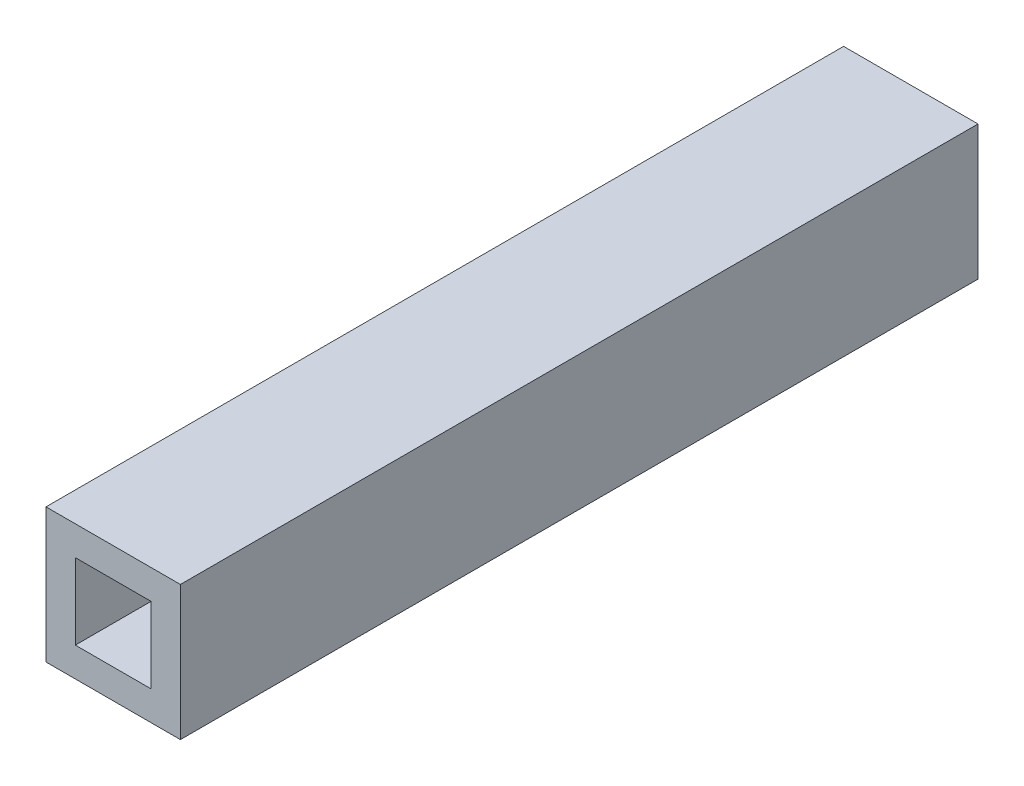
SolidWorks part; units mm, degrees
ref_plane "Front Plane" through (0, 0, 0) normal (0, 0, 1) x (1, 0, 0)
ref_plane "Top Plane" through (0, 0, 0) normal (0, 1, 0) x (1, 0, 0)
ref_plane "Right Plane" through (0, 0, 0) normal (1, 0, 0) x (0, 0, -1)
sketch "Sketch1" plane through (0, 0, 0) normal (0, 0, 1) x (1, 0, 0)
  line L1 (7.7358, 7.4308) -> (24.5858, 7.4308)
  line L2 (7.7358, 7.4308) -> (7.7358, -9.4192)
  line L3 (7.7358, -9.4192) -> (24.5858, -9.4192)
  line L4 (24.5858, 7.4308) -> (24.5858, -9.4192)
  line L5 (11.4108, 3.7558) -> (20.9108, 3.7558)
  line L6 (11.4108, 3.7558) -> (11.4108, -5.7442)
  line L7 (11.4108, -5.7442) -> (20.9108, -5.7442)
  line L8 (20.9108, 3.7558) -> (20.9108, -5.7442)
  point P11 (34.0854, 18.441)
  dimension "D1" = 16.85
  dimension "D2" = 16.85
  dimension "D3" = 9.5
  dimension "D4" = 9.5
  dimension "D5" = 3.675
  dimension "D6" = 3.675
extrude "Boss-Extrude1" add sketch "Sketch1" against normal blind 100
